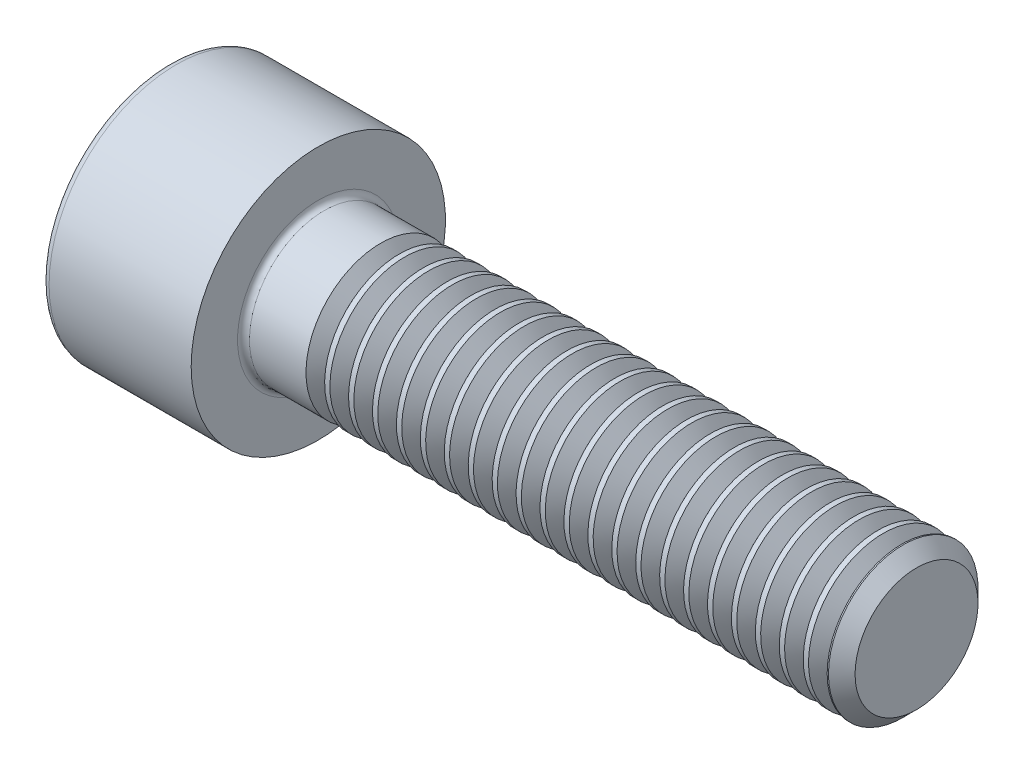
SolidWorks part; units mm, degrees
revolve "Base-Revolve" add sketch "BodySke"
sketch "BodySke" plane through (0, 0, 0) normal (0, 0, 1) x (1, 0, 0)
  line L0 (0, 0) -> (0, 4.25)
  line L1 (0, 4.25) -> (5, 4.25)
  line L2 (5, 4.25) -> (5, 2.5)
  line L3 (5, 2.5) -> (24.555, 2.5)
  line L4 (25, 2.055) -> (25, 0)
  line L5 (25, 0) -> (0, 0)
  line L6 (-31.75, 0) -> (127, 0) construction
  line L8 (25, 2.055) -> (24.555, 2.5)
  line L10 (25, -2.055) -> (24.555, -2.5) construction
  line L11 (5.8, 9.525) -> (5.8, 3.175) construction
  line L12 (5, 9.525) -> (5, 3.175) construction
  line L13 (-35, 9.525) -> (-35, 3.175) construction
  dimension "Head_ht" = 5
  dimension "Length" = 20
  dimension "Body_ch_ang" = 45
  dimension "Diameter" = 5
  dimension "Minor_dia" = 4.11
  dimension "Advance" = 0.8
  dimension "Thread_nom" = 20
  dimension "Thread_length" = 60
  dimension "Head_dia" = 8.5
cosmetic thread "ThreadCosmetic" [suppressed]
fillet "Fillet1" radius 0.2 1 edges at (5, 0, 2.5)
fillet "Fillet2" radius 0.25 1 edges at (0, 0, 4.25)
ref_plane "Plane1" through (0, 0, 0) normal (0, 0, 1) x (1, 0, 0)
ref_plane "Plane2" through (0, 0, 0) normal (0, 1, 0) x (1, 0, 0)
ref_plane "Plane3" through (0, 0, 0) normal (1, 0, 0) x (0, 0, -1)
sketch "Sketch2" plane through (0, 0, 0) normal (0, 0, 1) x (1, 0, 0)
  line L0 (0, 2.042) -> (2.5, 2.042)
  line L1 (2.5, 2.042) -> (3.6789, 0)
  line L2 (-31.75, 0) -> (127, 0) construction
  line L3 (3.6789, 0) -> (0, 0)
  line L4 (0, 0) -> (0, 2.042)
  line L6 (0, 0) -> (47.625, 0) construction
  dimension "D1" = 2.042
  dimension "D2" = 60
  dimension "Depth" = 2.5
revolve "Hex-PreBroach" cut sketch "Sketch2" angle 360 about L6
sketch "Sketch3" plane through (0, 0, 0) normal (-1, 0, 0) x (0, 0.5, 0.866)
  line L0 (1.1789, 2.042) -> (-1.1789, 2.042)
  line L1 (-1.1789, 2.042) -> (-2.3579, 0)
  line L2 (1.1789, 2.042) -> (2.3579, 0)
  line L3 (1.1789, -2.042) -> (2.3579, 0)
  line L4 (1.1789, -2.042) -> (-1.1789, -2.042)
  line L5 (-1.1789, -2.042) -> (-2.3579, 0)
  dimension "D1" = 2.042
  dimension "D2" = 2.042
  dimension "Hex_size" = 4.084
extrude "Hex" cut sketch "Sketch3" against normal blind 2.5
sketch "ThdSchSke" plane through (0, 0, 0) normal (0, 0, 1) x (1, 0, 0)
  line L0 (7.4, -2.055) -> (7.0884, -2.5)
  line L1 (7.4, -2.055) -> (7.7116, -2.5)
  line L2 (7.7116, -2.5) -> (7.7116, -3.125)
  line L3 (-3.175, 0) -> (5.1513, 0) construction
  line L4 (0, 4) -> (0, -4) construction
  line L5 (7.7116, -3.125) -> (7.0884, -3.125)
  line L6 (7.0884, -3.125) -> (7.0884, -2.5)
  dimension "Thread_minor" = 4.11
  dimension "Diameter" = 5
  dimension "Start" = 7.4
revolve "ThreadSchematic" cut sketch "ThdSchSke" angle 360 about L3
pattern_linear "ThdSchPat" count 22 spacing 0.8 along (1, 0, 0) of "ThreadSchematic"
equation "\"D2@Sketch3\" = \"Hex_size@Sketch3\" / 2"
equation "\"D1@Sketch3\" = \"Hex_size@Sketch3\" / 2"
equation "\"D1@Sketch2\" = \"Hex_size@Sketch3\" / 2"
equation "\"Thread_minor@ThreadCosmetic\"  =  \"Minor_dia@BodySke\""
equation "\"Depth@Sketch2\" =  \"Key_eng@Hex\""
equation "\"Thread_length@ThreadCosmetic\" = ((sgn( (\"Length@BodySke\" - \"Advance@BodySke\" * 3.0) - \"Thread_nom@BodySke\" )-1)*( (\"Length@BodySke\" - \"Advance@BodySke\" * 3.0) - \"Thread_nom@BodySke\" ))/-2+ \"Thread_nom@BodySke\""
equation "\"Thread_minor@ThdSchSke\" = \"Minor_dia@BodySke\""
equation "\"Diameter@ThdSchSke\" = \"Diameter@BodySke\""
equation "\"Overcut@ThdSchSke\" = \"Diameter@BodySke\" * 1.25"
equation "\"Start@ThdSchSke\" = \"Head_ht@BodySke\" + \"Length@BodySke\" - \"Thread_length@ThreadCosmetic\"  '---Non-countersunk---"
equation "\"Num_threads@ThdSchPat\" = int( \"Thread_length@ThreadCosmetic\" / \"Advance@BodySke\" + 0.999 )  + 1"
equation "\"Advance@ThdSchPat\" = \"Thread_length@ThreadCosmetic\" /  (\"Num_threads@ThdSchPat\" - 1) 'relax it"
equation "\"Num_threads@ThdSchPat\" = \"Num_threads@ThdSchPat\" - sgn( \"Num_threads@ThdSchPat\" - 1) '---chamfered tips only---"
